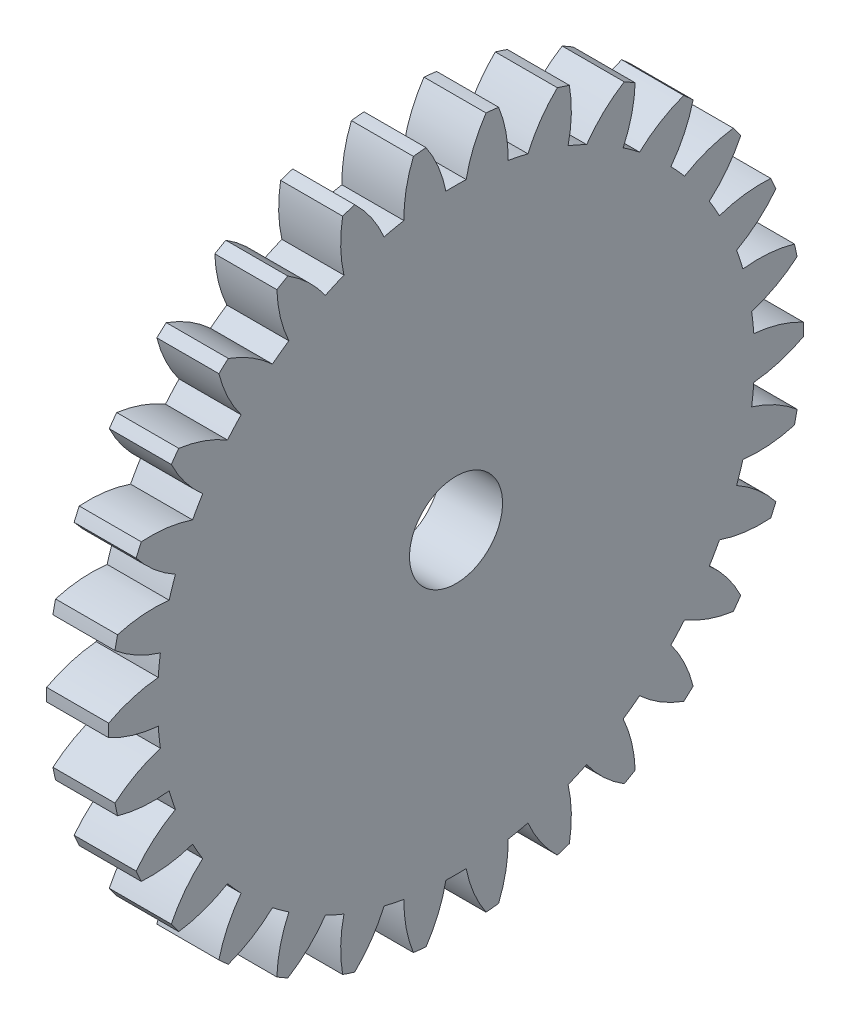
SolidWorks part; units mm, degrees
material "AISI 347 Annealed Stainless Steel (SS)"
ref_plane "Plane1" through (0, 0, 0) normal (0, 0, 1) x (1, 0, 0)
ref_plane "Plane2" through (0, 0, 0) normal (0, 1, 0) x (1, 0, 0)
ref_plane "Plane3" through (0, 0, 0) normal (1, 0, 0) x (0, 0, -1)
sketch "HoldingSke" plane through (0, 0, 0) normal (0, 1, 0) x (1, 0, 0)
  line L0 (0, 0) -> (1.2372, -0.7143)
  line L1 (-15, 0) -> (100, 0) construction
  line L2 (0, 0) -> (-2.1039, 2.3779)
  line L3 (0, 0) -> (-11.863, 4.5341)
  line L4 (0, 0) -> (7.479, 4.318)
  line L5 (0, 0) -> (-46.8476, -17.4728)
  line L6 (0, 0) -> (-1.6579, -1.1186)
  line L7 (-2.1039, 2.3779) -> (8.6586, 51.2059)
  line L8 (-76.2, 54.61) -> (-75.7, 54.61)
  line L9 (-71.009, 38.7566) -> (-53.1078, 45.2721)
  line L10 (-76.2, 71.12) -> (104.1128, 71.12)
  line L11 (0, 0) -> (-2, 0)
  line L12 (-76.2, 101.6) -> (-76.173, 101.6)
  line L13 (24.9733, 27.94) -> (52.9518, 28.4284)
  line L14 (24.9733, 27.94) -> (24.9743, 27.94)
  line L15 (24.9733, 27.94) -> (100.4006, 29.5858)
  line L16 (-63.627, -0.7) -> (-12.827, -0.7)
  circle A0 centre (0, 0) radius 1.5
  circle A1 centre (0, 0) radius 9.624
  circle A2 centre (0, 0) radius 37.5
  circle A3 centre (0, 0) radius 1.5
  dimension "MHD" = 19.248
  dimension "Hub_dia" = 75
  dimension "Bore" = 3
  dimension "MBD" = 3
  dimension "Num_teeth" = 30
  dimension "Pitch" = 1.4286
  dimension "Overall_len" = 50
  dimension "Show_teeth" = 30
  dimension "Thickness" = 2
  dimension "OAL" = 50.0001
  dimension "T_dim" = 0.5
  dimension "Ap" = 20
  dimension "H" = 19.05
  dimension "Pitch_radius" = 180.3128
  dimension "Width" = 2
  dimension "Backlash" = 0.027
  dimension "Addendum_fac" = 1
  dimension "Dedendum_fac" = 1.25
  dimension "Clearance_fac" = 0.25
  dimension "Dedendum_add" = 0.001
  dimension "Module" = 0.7
sketch "BasProSke" plane through (0, 0, 0) normal (0, 1, 0) x (1, 0, 0)
  line L0 (-10, 0) -> (60, 0) construction
  line L1 (0, 0) -> (0, 11.2)
  line L2 (0, 0) -> (2, 0)
  line L3 (2, 0) -> (2, 11.2)
  line L4 (2, 11.2) -> (0, 11.2)
  dimension "Thickness" = 2
  dimension "Diameter" = 22.4
revolve "Base-Revolve" add sketch "BasProSke" angle 360 about L0
sketch "TooCutSke" plane through (0, 0, 0) normal (1, 0, 0) x (0, 0, -1)
  line L1 (0, 0) -> (0, 107) construction
  line L2 (0, 0) -> (-0.5968, 10.483) construction
  line L3 (0, 0) -> (-2.1926, 20.8611) construction
  line L4 (-0.5968, 10.483) -> (-1.0963, 10.4305) construction
  arc A0 (0.3271, 9.6184) -> (-0.3271, 9.6184) centre (0, 0) ccw
  arc A1 (0.9839, 11.1822) -> (-0.9839, 11.1822) centre (0, 0) ccw
  circle A2 centre (0, 0) radius 10.5 construction
  circle A3 centre (0, 0) radius 9.8668 construction
  arc A4 (-0.3271, 9.6184) -> (-0.9839, 11.1822) centre (-4.448, 8.8073) ccw
  arc A5 (0.9839, 11.1822) -> (0.3271, 9.6184) centre (4.448, 8.8073) ccw
  dimension "Root_dia" = 19.248
  dimension "Overcut_dia" = 22.4508
  dimension "Pitch_dia" = 21
  dimension "Base_dia" = 19.7335
  dimension "Flank_rad" = 4.2
  dimension "Half_ang" = 6
  dimension "Half_CT" = 0.5023
extrude "ToothCut" cut sketch "TooCutSke" along normal through all
fillet "Breaks" [suppressed] radius 0.014
fillet "RootFillets" [suppressed] radius 0.176
pattern_circular "TeethCuts" count 30 every 12 about axis through (-10, 0, 0) along (1, 0, 0) of "ToothCut", "RootFillets", "Breaks"
sketch "HubNeaOneSke" plane through (0, 0, 0) normal (-1, 0, 0) x (0, 0, 1)
  circle A0 centre (0, 0) radius 9.624
  dimension "Diameter" = 19.248
extrude "HubNearOne" [suppressed] add sketch "HubNeaOneSke" along normal blind 48.0001
sketch "HubNeaBotSke" plane through (0, 0, 0) normal (-1, 0, 0) x (0, 0, 1)
  circle A0 centre (0, 0) radius 9.624
  dimension "Diameter" = 19.248
extrude "HubNearBoth" [suppressed] add sketch "HubNeaBotSke" along normal blind 24
ref_plane "FarPln" through (2, 0, 0) normal (1, 0, 0) x (0, 0, -1)
sketch "HubFarSke" plane through (2, 0, 0) normal (1, 0, 0) x (0, 0, -1)
  circle A0 centre (0, 0) radius 9.624
  dimension "Diameter" = 19.248
extrude "HubFar" [suppressed] add sketch "HubFarSke" along normal blind 24
sketch "BorSke" plane through (0, 0, 0) normal (1, 0, 0) x (0, 0, -1)
  circle A0 centre (0, 0) radius 1.5
  dimension "Diameter" = 3
extrude "Bore" cut sketch "BorSke" along normal mid plane 100.0001
sketch "KeySke" plane through (0, 0, 0) normal (1, 0, 0) x (0, 0, -1)
  line L0 (-0.6, 0) -> (-0.6, 2)
  line L1 (-0.6, 2) -> (0.6, 2)
  line L2 (0.6, 2) -> (0.6, 0)
  line L3 (0, 0) -> (0, 34) construction
  line L4 (-0.6, 0) -> (0.6, 0)
  dimension "Offset" = 2
  dimension "Width" = 1.2
extrude "Keyway" [suppressed] cut sketch "KeySke" along normal mid plane 100.0001
pattern_circular "Keyway2" [suppressed] count 2 every 90 about axis through (-10, 0, 0) along (1, 0, 0)
equation "' \"Module@HoldingSke\" = 6.35"
equation "' \"Num_teeth@HoldingSke\" = 12"
equation "' \"Ap@HoldingSke\" =  20"
equation "' \"Ap@HoldingSke\" = 20"
equation "' \"Width@HoldingSke\" = 0.5 * 25.4"
equation "' \"Hub_dia@HoldingSke\"= 1 * 25.4"
equation "' \"Hub_dia@HoldingSke\" = 1 * 25.4"
equation "' \"Overall_len@HoldingSke\" = 1.0 * 25.4"
equation "' \"Bore@HoldingSke\" = 0.75 * 25.4"
equation "' \"T_dim@HoldingSke\" = 0.1 * 25.4"
equation "' \"Width@KeySke\" = 0.25 * 25.4"
equation "' \"Show_teeth@HoldingSke\" = 13"
equation "' \"Backlash@HoldingSke\" = 0.009 * 25.4"
equation "' \"Addendum_fac@HoldingSke\" = 1.0"
equation "' \"Dedendum_fac@HoldingSke\" = 1.25"
equation "' \"Dedendum_add@HoldingSke\" = 0.00005 * 25.4"
equation "' \"Clearance_fac@HoldingSke\" = 0.25"
equation "\"Pitch@HoldingSke\" = 1 / \"Module@HoldingSke\""
equation "\"Overcut_dia@TooCutSke\" = (\"Num_teeth@HoldingSke\" + 2 * \"Addendum_fac@HoldingSke\") / \"Pitch@HoldingSke\" + 0.002 * 25.4"
equation "\"Pitch_dia@TooCutSke\" = \"Num_teeth@HoldingSke\" / \"Pitch@HoldingSke\""
equation "\"Base_dia@TooCutSke\" = \"Num_teeth@HoldingSke\" / \"Pitch@HoldingSke\" * cos((\"Ap@HoldingSke\"  * 3.14159265 / 180))"
equation "\"Root_dia@TooCutSke\" = (\"Num_teeth@HoldingSke\" + 2) / \"Pitch@HoldingSke\" - 2 * (\"Addendum_fac@HoldingSke\" + \"Dedendum_fac@HoldingSke\") / \"Pitch@HoldingSke\" - \"Dedendum_add@HoldingSke\" * 2"
equation "\"Half_ang@TooCutSke\" = 180 / \"Num_teeth@HoldingSke\""
equation "\"Half_CT@TooCutSke\" = \"Num_teeth@HoldingSke\" / \"Pitch@HoldingSke\" * sin((3.14159265 / 2 / \"Num_teeth@HoldingSke\")) / 2 - 7 * \"Backlash@HoldingSke\" / 4"
equation "\"Flank_rad@TooCutSke\" = \"Num_teeth@HoldingSke\" / \"Pitch@HoldingSke\" / 5"
equation "\"Radius@RootFillets\" = \"Clearance_fac@HoldingSke\" / \"Pitch@HoldingSke\" + \"Dedendum_add@HoldingSke\""
equation "\"Break_rad@Breaks\" = 0.02 / \"Pitch@HoldingSke\""
equation "\"Thickness@HoldingSke\" = \"Width@HoldingSke\""
equation "\"OAL@HoldingSke\" = \"Thickness@HoldingSke\""
equation "\"MHD@HoldingSke\" = (\"Num_teeth@HoldingSke\" + 2) / \"Pitch@HoldingSke\" - 2 * (\"Addendum_fac@HoldingSke\" + \"Dedendum_fac@HoldingSke\")  / \"Pitch@HoldingSke\" - \"Dedendum_add@HoldingSke\" * 2"
equation "\"MBD@HoldingSke\" = (\"Num_teeth@HoldingSke\" + 2) / \"Pitch@HoldingSke\" - 2 * (\"Addendum_fac@HoldingSke\" + \"Dedendum_fac@HoldingSke\")  / \"Pitch@HoldingSke\" - \"Dedendum_add@HoldingSke\" * 2 - 0.002 * 25.4"
equation "\"MHD@HoldingSke\" = ((sgn( \"MHD@HoldingSke\" - \"Hub_dia@HoldingSke\" )-1)*( \"MHD@HoldingSke\" - \"Hub_dia@HoldingSke\" ))/-2+ \"Hub_dia@HoldingSke\""
equation "\"MBD@HoldingSke\" = ((sgn( \"MBD@HoldingSke\" - \"Bore@HoldingSke\" )-1)*( \"MBD@HoldingSke\" - \"Bore@HoldingSke\" ))/-2+ \"Bore@HoldingSke\""
equation "\"OAL@HoldingSke\" = ((sgn( \"OAL@HoldingSke\" - \"Overall_len@HoldingSke\" )+1)*( \"OAL@HoldingSke\" - \"Overall_len@HoldingSke\" ))/2 + \"Overall_len@HoldingSke\" + 0.000002 * 25.4"
equation "\"Num_teeth@TeethCuts\" = int( \"Show_teeth@HoldingSke\" ) + 1"
equation "\"Num_teeth@TeethCuts\" = ((sgn( \"Num_teeth@TeethCuts\" - \"Num_teeth@HoldingSke\" )-1)*( \"Num_teeth@TeethCuts\" - \"Num_teeth@HoldingSke\" ))/-2+ \"Num_teeth@HoldingSke\""
equation "\"Num_teeth@TeethCuts\" = ((sgn( \"Num_teeth@TeethCuts\" - 2.0)+1)*( \"Num_teeth@TeethCuts\" - 2.0))/2 +2.0"
equation "\"Angle@TeethCuts\" = 360.0 / \"Num_teeth@HoldingSke\""
equation "\"Diameter@BasProSke\" = (\"Num_teeth@HoldingSke\" + 2 * \"Addendum_fac@HoldingSke\") / \"Pitch@HoldingSke\""
equation "\"Thickness@BasProSke\"  = \"Thickness@HoldingSke\""
equation "' \"Fillet_rad@BasProSke\" =  \"Thickness@HoldingSke\" * 0.05"
equation "' \"Fillet_rad@BasProSke\" = \"Thickness@HoldingSke\" * 0.05"
equation "\"MHD@HoldingSke\" = ((sgn( \"MHD@HoldingSke\" - \"Root_dia@TooCutSke\" )-1)*( \"MHD@HoldingSke\" - \"Root_dia@TooCutSke\" ))/-2+ \"Root_dia@TooCutSke\""
equation "\"Diameter@HubNeaOneSke\" = \"MHD@HoldingSke\""
equation "\"Length@HubNearOne\" = \"OAL@HoldingSke\" - \"Thickness@BasProSke\""
equation "\"Diameter@HubNeaBotSke\" = \"MHD@HoldingSke\""
equation "\"Length@HubNearBoth\" = ( \"OAL@HoldingSke\" - \"Thickness@BasProSke\" ) / 2.0"
equation "\"Thickness@FarPln\" = \"Thickness@BasProSke\""
equation "\"Diameter@HubFarSke\" = \"MHD@HoldingSke\""
equation "\"Length@HubFar\" = ( \"OAL@HoldingSke\" - \"Thickness@BasProSke\" ) / 2.0"
equation "\"Diameter@BorSke\" = \"MBD@HoldingSke\""
equation "\"D1@Bore\" = \"OAL@HoldingSke\" * 2.0"
equation "\"D1@Keyway\" = \"OAL@HoldingSke\" * 2.0"
equation "\"Offset@KeySke\" = \"T_dim@HoldingSke\" + \"MBD@HoldingSke\" / 2.0"
